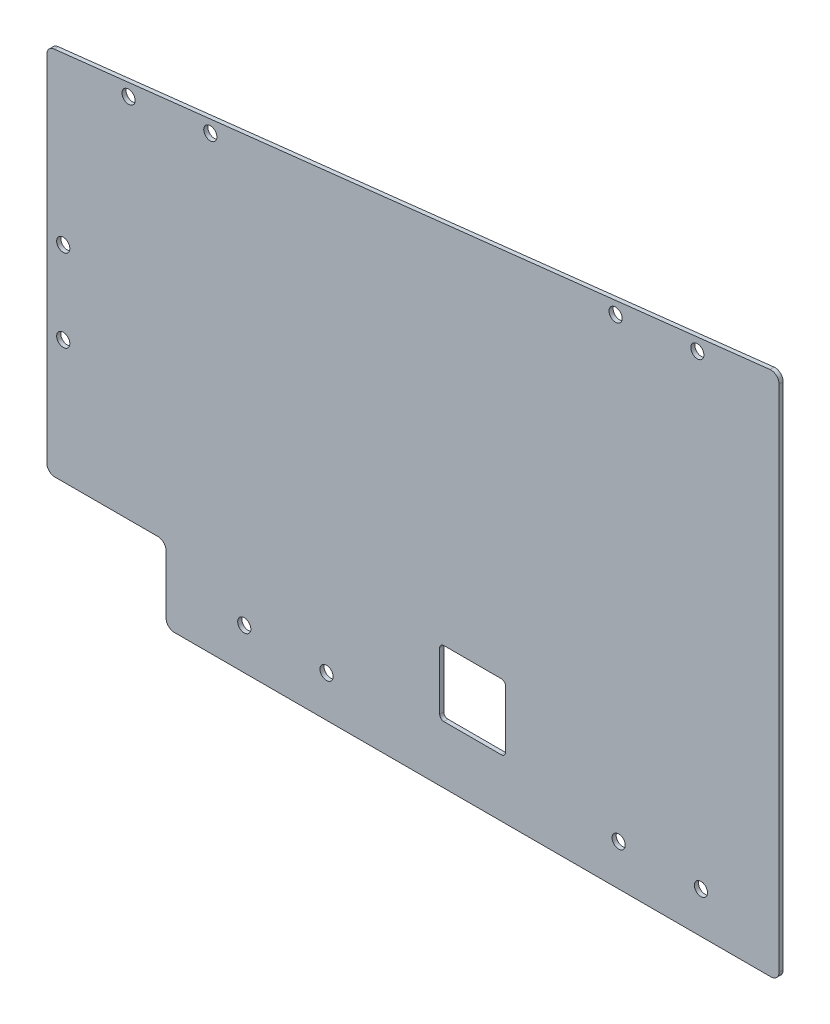
SolidWorks part; units mm, degrees
material "Thornel Mat VMA"
ref_plane "前视基准面" through (0, 0, 0) normal (0, 0, 1) x (1, 0, 0)
ref_plane "上视基准面" through (0, 0, 0) normal (0, 1, 0) x (1, 0, 0)
ref_plane "右视基准面" through (0, 0, 0) normal (1, 0, 0) x (0, 0, -1)
other "Configuration Table"
sketch "草图1" plane through (0, 0, 0) normal (0, 0, 1) x (1, 0, 0)
  line L0 (-10, 0) -> (10, 0) construction
  line L1 (0, 0) -> (0, -50000) construction
  line L3 (-45, -10) -> (45, -10)
  line L4 (-45, -10) -> (-45, 4)
  line L5 (-45, 4) -> (45, 4)
  line L6 (45, -10) -> (45, 4)
  line L7 (-45, -10) -> (45, 4) construction
  line L8 (-45, 4) -> (45, -10) construction
  point P4 (0, 0)
  point P8 (0, -3)
  dimension "D1" = 10
  dimension "D2" = 20
  dimension "D4" = 4
  dimension "D5" = 90
extrude "凸台-拉伸1" add sketch "草图1" along normal blind 1
sketch "草图2" plane through (0, 0, 1) normal (0, 0, 1) x (1, 0, 0)
  line L0 (45, 4) -> (-45, 4) construction
  line L2 (-85, 8.2) -> (-85, 4)
  line L3 (-85, 4) -> (64, 4)
  line L4 (64, 118) -> (64, 4)
  line L5 (-114, 98) -> (64, 118)
  line L6 (-85, 8.2) -> (-114, 8.2)
  line L9 (-114, 8.2) -> (-114, 98)
  line L10 (45, -10) -> (45, 4) construction
  line L11 (-45, 4) -> (-45, -10) construction
  dimension "D1" = 19
  dimension "D2" = 40
  dimension "D3" = 29
  dimension "D4" = 4.2
  dimension "D5" = 114
  dimension "D6" = 94
extrude "凸台-拉伸2" add sketch "草图2" against normal blind 1
sketch "草图4" plane through (0, 0, 1) normal (0, 0, 1) x (1, 0, 0)
  line L1 (-85, 4) -> (-45, 4)
  line L2 (-85, 4) -> (-85, -10)
  line L3 (-85, -10) -> (-45, -10)
  line L4 (-45, 4) -> (-45, -10)
  line L5 (64, 4) -> (45, 4)
  line L6 (64, 4) -> (64, -10)
  line L7 (64, -10) -> (45, -10)
  line L8 (45, 4) -> (45, -10)
extrude "凸台-拉伸3" add sketch "草图4" against normal up to surface (1 mm away) up to face at (-27, 22.84, 0)
sketch "草图7" plane through (0, 0, 1) normal (0, 0, 1) x (1, 0, 0)
  line L0 (-85, 0) -> (64, 0) construction
  line L1 (-85, 8.2) -> (-85, -10) construction
  line L2 (64, 118) -> (64, -10) construction
  line L3 (-85, -10) -> (64, -10) construction
  circle A0 centre (45, 0) radius 1.6
  circle A1 centre (25, 0) radius 1.6
  circle A2 centre (-66, 0) radius 1.6
  circle A3 centre (-46, 0) radius 1.6
  dimension "D2" = 3.2
  dimension "D3" = 20
  dimension "D4" = 19
  dimension "D5" = 20
  dimension "D1" = 10
  dimension "D6" = 19
extrude "切除-拉伸1" cut sketch "草图7" against normal blind 10
sketch "草图8" plane through (0, 0, 1) normal (0, 0, 1) x (1, 0, 0)
  line L1 (64, 118) -> (64, -10) construction
  line L2 (-113.665, 95.0188) -> (64.335, 115.0188)
  line L3 (-114, 94.9811) -> (64, 114.9811) construction
  line L4 (-114, 8.2) -> (-114, 98) construction
  circle A0 centre (-94.1251, 97.2143) radius 1.6
  circle A1 centre (-74.2501, 99.4474) radius 1.6
  circle A2 centre (24.2501, 110.5148) radius 1.6
  circle A3 centre (44.1251, 112.748) radius 1.6
  dimension "D2" = 3.2
  dimension "D3" = 20
  dimension "D4" = 20
  dimension "D5" = 20
  dimension "D6" = 20
  dimension "D1" = 3
extrude "切除-拉伸2" cut sketch "草图8" against normal blind 10
sketch "草图9" plane through (0, 0, 0) normal (0, 0, -1) x (-1, 0, 0)
  line L0 (110, 8.2) -> (110, 98.4494) construction
  line L1 (85, 8.2) -> (114, 8.2) construction
  line L2 (114, 98) -> (-64, 118) construction
  line L3 (114, 8.2) -> (114, 98) construction
  line L4 (115, 53.1) -> (50115, 53.1) construction
  circle A0 centre (110, 58.1) radius 1.6
  circle A1 centre (110, 38.1) radius 1.6
  point P14 (114, 53.1)
  dimension "D2" = 3.2
  dimension "D3" = 20
  dimension "D4" = 5
  dimension "D1" = 4
extrude "切除-拉伸3" cut sketch "草图9" against normal blind 10
fillet "圆角1" radius 2 6 edges at (64, -10, 0.5) (64, 118, 0.5) (-114, 98, 0.5) (-85, -10, 0.5) (-85, 8.2, 0.5) (-114, 8.2, 0.5)
sketch "草图10" plane through (0, 0, 1) normal (0, 0, 1) x (1, 0, 0)
  line L0 (-46, 0) -> (25, 0) construction
  line L1 (-10.5, 12) -> (-10.5, -10) construction
  line L2 (-18.5, 4) -> (-2.5, 4)
  line L3 (-18.5, 4) -> (-18.5, 20)
  line L4 (-18.5, 20) -> (-2.5, 20)
  line L5 (-2.5, 4) -> (-2.5, 20)
  line L6 (-18.5, 4) -> (-2.5, 20) construction
  line L7 (-18.5, 20) -> (-2.5, 4) construction
  line L8 (-83, -10) -> (62, -10) construction
  circle A0 centre (-10.5, 12) radius 8 construction
  point P4 (-10.5, 12)
  dimension "D1" = 16
  dimension "D2" = 14
extrude "切除-拉伸4" cut sketch "草图10" against normal blind 10
fillet "圆角2" radius 1 4 edges at (-18.5, 4, 0.5) (-18.5, 20, 0.5) (-2.5, 20, 0.5) (-2.5, 4, 0.5)
